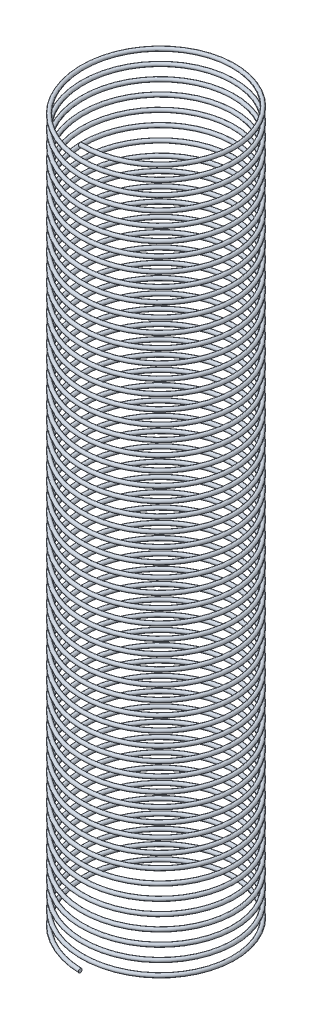
SolidWorks part; units mm, degrees
ref_plane "Front Plane" through (0, 0, 0) normal (0, 0, 1) x (1, 0, 0)
ref_plane "Top Plane" through (0, 0, 0) normal (0, 1, 0) x (1, 0, 0)
ref_plane "Right Plane" through (0, 0, 0) normal (1, 0, 0) x (0, 0, -1)
sketch "Sketch1" plane through (0, 0, 0) normal (0, 1, 0) x (1, 0, 0)
  circle A0 centre (0, 0) radius 2
  dimension "D1" = 4
curve "Helix/Spiral1" pitch 0.35 height 18.9 turns 54
sketch "Sketch2" plane through (0, 0, 0) normal (1, 0, 0) x (0, 0, -1)
  circle A0 centre (-2, 0) radius 0.05
  spline S0 degree 3 poles (-2, 0) (-2, 0.0072) (-1.8959, 0.0219) (-1.451, 0.0437) (-0.7853, 0.0656) (0, 0.0875) (0.7853, 0.1094) (1.451, 0.1312) (1.8959, 0.1531) (2.0521, 0.175) (1.8959, 0.1969) (1.451, 0.2187) (0.7853, 0.2406) (0, 0.2625) (-0.7853, 0.2844) (-1.451, 0.3062) (-1.8959, 0.3281) (-2.0521, 0.35) (-1.8959, 0.3719) (-1.451, 0.3937) (-0.7853, 0.4156) (0, 0.4375) (0.7853, 0.4594) (1.451, 0.4812) (1.8959, 0.5031) (2.0521, 0.525) (1.8959, 0.5469) (1.451, 0.5687) (0.7853, 0.5906) (0, 0.6125) (-0.7853, 0.6344) (-1.451, 0.6562) (-1.8959, 0.6781) (-2.0521, 0.7) (-1.8959, 0.7219) (-1.451, 0.7437) (-0.7853, 0.7656) (0, 0.7875) (0.7853, 0.8094) (1.451, 0.8312) (1.8959, 0.8531) (2.0521, 0.875) (1.8959, 0.8969) (1.451, 0.9187) (0.7853, 0.9406) (0, 0.9625) (-0.7853, 0.9844) (-1.451, 1.0062) (-1.8959, 1.0281) (-2.0521, 1.05) (-1.8959, 1.0719) (-1.451, 1.0937) (-0.7853, 1.1156) (0, 1.1375) (0.7853, 1.1594) (1.451, 1.1812) (1.8959, 1.2031) (2.0521, 1.225) (1.8959, 1.2469) (1.451, 1.2687) (0.7853, 1.2906) (0, 1.3125) (-0.7853, 1.3344) (-1.451, 1.3562) (-1.8959, 1.3781) (-2.0521, 1.4) (-1.8959, 1.4219) (-1.451, 1.4437) (-0.7853, 1.4656) (0, 1.4875) (0.7853, 1.5094) (1.451, 1.5312) (1.8959, 1.5531) (2.0521, 1.575) (1.8959, 1.5969) (1.451, 1.6187) (0.7853, 1.6406) (0, 1.6625) (-0.7853, 1.6844) (-1.451, 1.7062) (-1.8959, 1.7281) (-2.0521, 1.75) (-1.8959, 1.7719) (-1.451, 1.7937) (-0.7853, 1.8156) (0, 1.8375) (0.7853, 1.8594) (1.451, 1.8812) (1.8959, 1.9031) (2.0521, 1.925) (1.8959, 1.9469) (1.451, 1.9687) (0.7853, 1.9906) (0, 2.0125) (-0.7853, 2.0344) (-1.451, 2.0562) (-1.8959, 2.0781) (-2.0521, 2.1) (-1.8959, 2.1219) (-1.451, 2.1437) (-0.7853, 2.1656) (0, 2.1875) (0.7853, 2.2094) (1.451, 2.2313) (1.8959, 2.2531) (2.0521, 2.275) (1.8959, 2.2969) (1.451, 2.3188) (0.7853, 2.3406) (0, 2.3625) (-0.7853, 2.3844) (-1.451, 2.4063) (-1.8959, 2.4281) (-2.0521, 2.45) (-1.8959, 2.4719) (-1.451, 2.4938) (-0.7853, 2.5156) (0, 2.5375) (0.7853, 2.5594) (1.451, 2.5813) (1.8959, 2.6031) (2.0521, 2.625) (1.8959, 2.6469) (1.451, 2.6688) (0.7853, 2.6906) (0, 2.7125) (-0.7853, 2.7344) (-1.451, 2.7563) (-1.8959, 2.7781) (-2.0521, 2.8) (-1.8959, 2.8219) (-1.451, 2.8438) (-0.7853, 2.8656) (0, 2.8875) (0.7853, 2.9094) (1.451, 2.9313) (1.8959, 2.9531) (2.0521, 2.975) (1.8959, 2.9969) (1.451, 3.0188) (0.7853, 3.0406) (0, 3.0625) (-0.7853, 3.0844) (-1.451, 3.1063) (-1.8959, 3.1281) (-2.0521, 3.15) (-1.8959, 3.1719) (-1.451, 3.1938) (-0.7853, 3.2156) (0, 3.2375) (0.7853, 3.2594) (1.451, 3.2813) (1.8959, 3.3031) (2.0521, 3.325) (1.8959, 3.3469) (1.451, 3.3688) (0.7853, 3.3906) (0, 3.4125) (-0.7853, 3.4344) (-1.451, 3.4563) (-1.8959, 3.4781) (-2.0521, 3.5) (-1.8959, 3.5219) (-1.451, 3.5438) (-0.7853, 3.5656) (0, 3.5875) (0.7853, 3.6094) (1.451, 3.6313) (1.8959, 3.6531) (2.0521, 3.675) (1.8959, 3.6969) (1.451, 3.7188) (0.7853, 3.7406) (0, 3.7625) (-0.7853, 3.7844) (-1.451, 3.8063) (-1.8959, 3.8281) (-2.0521, 3.85) (-1.8959, 3.8719) (-1.451, 3.8938) (-0.7853, 3.9156) (0, 3.9375) (0.7853, 3.9594) (1.451, 3.9813) (1.8959, 4.0031) (2.0521, 4.025) (1.8959, 4.0469) (1.451, 4.0688) (0.7853, 4.0906) (0, 4.1125) (-0.7853, 4.1344) (-1.451, 4.1563) (-1.8959, 4.1781) (-2.0521, 4.2) (-1.8959, 4.2219) (-1.451, 4.2438) (-0.7853, 4.2656) (0, 4.2875) (0.7853, 4.3094) (1.451, 4.3313) (1.8959, 4.3531) (2.0521, 4.375) (1.8959, 4.3969) (1.451, 4.4188) (0.7853, 4.4406) (0, 4.4625) (-0.7853, 4.4844) (-1.451, 4.5063) (-1.8959, 4.5281) (-2.0521, 4.55) (-1.8959, 4.5719) (-1.451, 4.5938) (-0.7853, 4.6156) (0, 4.6375) (0.7853, 4.6594) (1.451, 4.6813) (1.8959, 4.7031) (2.0521, 4.725) (1.8959, 4.7469) (1.451, 4.7688) (0.7853, 4.7906) (0, 4.8125) (-0.7853, 4.8344) (-1.451, 4.8563) (-1.8959, 4.8781) (-2.0521, 4.9) (-1.8959, 4.9219) (-1.451, 4.9438) (-0.7853, 4.9656) (0, 4.9875) (0.7853, 5.0094) (1.451, 5.0313) (1.8959, 5.0531) (2.0521, 5.075) (1.8959, 5.0969) (1.451, 5.1188) (0.7853, 5.1406) (0, 5.1625) (-0.7853, 5.1844) (-1.451, 5.2063) (-1.8959, 5.2281) (-2.0521, 5.25) (-1.8959, 5.2719) (-1.451, 5.2938) (-0.7853, 5.3156) (0, 5.3375) (0.7853, 5.3594) (1.451, 5.3813) (1.8959, 5.4031) (2.0521, 5.425) (1.8959, 5.4469) (1.451, 5.4688) (0.7853, 5.4906) (0, 5.5125) (-0.7853, 5.5344) (-1.451, 5.5563) (-1.8959, 5.5781) (-2.0521, 5.6) (-1.8959, 5.6219) (-1.451, 5.6438) (-0.7853, 5.6656) (0, 5.6875) (0.7853, 5.7094) (1.451, 5.7313) (1.8959, 5.7531) (2.0521, 5.775) (1.8959, 5.7969) (1.451, 5.8188) (0.7853, 5.8406) (0, 5.8625) (-0.7853, 5.8844) (-1.451, 5.9063) (-1.8959, 5.9281) (-2.0521, 5.95) (-1.8959, 5.9719) (-1.451, 5.9938) (-0.7853, 6.0156) (0, 6.0375) (0.7853, 6.0594) (1.451, 6.0813) (1.8959, 6.1031) (2.0521, 6.125) (1.8959, 6.1469) (1.451, 6.1688) (0.7853, 6.1906) (0, 6.2125) (-0.7853, 6.2344) (-1.451, 6.2563) (-1.8959, 6.2781) (-2.0521, 6.3) (-1.8959, 6.3219) (-1.451, 6.3438) (-0.7853, 6.3656) (0, 6.3875) (0.7853, 6.4094) (1.451, 6.4313) (1.8959, 6.4531) (2.0521, 6.475) (1.8959, 6.4969) (1.451, 6.5188) (0.7853, 6.5406) (0, 6.5625) (-0.7853, 6.5844) (-1.451, 6.6063) (-1.8959, 6.6281) (-2.0521, 6.65) (-1.8959, 6.6719) (-1.451, 6.6938) (-0.7853, 6.7156) (0, 6.7375) (0.7853, 6.7594) (1.451, 6.7813) (1.8959, 6.8031) (2.0521, 6.825) (1.8959, 6.8469) (1.451, 6.8688) (0.7853, 6.8906) (0, 6.9125) (-0.7853, 6.9344) (-1.451, 6.9563) (-1.8959, 6.9781) (-2.0521, 7) (-1.8959, 7.0219) (-1.451, 7.0438) (-0.7853, 7.0656) (0, 7.0875) (0.7853, 7.1094) (1.451, 7.1313) (1.8959, 7.1531) (2.0521, 7.175) (1.8959, 7.1969) (1.451, 7.2188) (0.7853, 7.2406) (0, 7.2625) (-0.7853, 7.2844) (-1.451, 7.3063) (-1.8959, 7.3281) (-2.0521, 7.35) (-1.8959, 7.3719) (-1.451, 7.3938) (-0.7853, 7.4156) (0, 7.4375) (0.7853, 7.4594) (1.451, 7.4813) (1.8959, 7.5031) (2.0521, 7.525) (1.8959, 7.5469) (1.451, 7.5688) (0.7853, 7.5906) (0, 7.6125) (-0.7853, 7.6344) (-1.451, 7.6563) (-1.8959, 7.6781) (-2.0521, 7.7) (-1.8959, 7.7219) (-1.451, 7.7438) (-0.7853, 7.7656) (0, 7.7875) (0.7853, 7.8094) (1.451, 7.8313) (1.8959, 7.8531) (2.0521, 7.875) (1.8959, 7.8969) (1.451, 7.9188) (0.7853, 7.9406) (0, 7.9625) (-0.7853, 7.9844) (-1.451, 8.0063) (-1.8959, 8.0281) (-2.0521, 8.05) (-1.8959, 8.0719) (-1.451, 8.0938) (-0.7853, 8.1156) (0, 8.1375) (0.7853, 8.1594) (1.451, 8.1813) (1.8959, 8.2031) (2.0521, 8.225) (1.8959, 8.2469) (1.451, 8.2688) (0.7853, 8.2906) (0, 8.3125) (-0.7853, 8.3344) (-1.451, 8.3563) (-1.8959, 8.3781) (-2.0521, 8.4) (-1.8959, 8.4219) (-1.451, 8.4438) (-0.7853, 8.4656) (0, 8.4875) (0.7853, 8.5094) (1.451, 8.5313) (1.8959, 8.5531) (2.0521, 8.575) (1.8959, 8.5969) (1.451, 8.6188) (0.7853, 8.6406) (0, 8.6625) (-0.7853, 8.6844) (-1.451, 8.7063) (-1.8959, 8.7281) (-2.0521, 8.75) (-1.8959, 8.7719) (-1.451, 8.7938) (-0.7853, 8.8156) (0, 8.8375) (0.7853, 8.8594) (1.451, 8.8813) (1.8959, 8.9031) (2.0521, 8.925) (1.8959, 8.9469) (1.451, 8.9688) (0.7853, 8.9906) (0, 9.0125) (-0.7853, 9.0344) (-1.451, 9.0563) (-1.8959, 9.0781) (-2.0521, 9.1) (-1.8959, 9.1219) (-1.451, 9.1438) (-0.7853, 9.1656) (0, 9.1875) (0.7853, 9.2094) (1.451, 9.2313) (1.8959, 9.2531) (2.0521, 9.275) (1.8959, 9.2969) (1.451, 9.3188) (0.7853, 9.3406) (0, 9.3625) (-0.7853, 9.3844) (-1.451, 9.4062) (-1.8959, 9.4281) (-2.0521, 9.45) (-1.8959, 9.4719) (-1.451, 9.4937) (-0.7853, 9.5156) (0, 9.5375) (0.7853, 9.5594) (1.451, 9.5812) (1.8959, 9.6031) (2.0521, 9.625) (1.8959, 9.6469) (1.451, 9.6687) (0.7853, 9.6906) (0, 9.7125) (-0.7853, 9.7344) (-1.451, 9.7562) (-1.8959, 9.7781) (-2.0521, 9.8) (-1.8959, 9.8219) (-1.451, 9.8437) (-0.7853, 9.8656) (0, 9.8875) (0.7853, 9.9094) (1.451, 9.9312) (1.8959, 9.9531) (2.0521, 9.975) (1.8959, 9.9969) (1.451, 10.0187) (0.7853, 10.0406) (0, 10.0625) (-0.7853, 10.0844) (-1.451, 10.1062) (-1.8959, 10.1281) (-2.0521, 10.15) (-1.8959, 10.1719) (-1.451, 10.1937) (-0.7853, 10.2156) (0, 10.2375) (0.7853, 10.2594) (1.451, 10.2812) (1.8959, 10.3031) (2.0521, 10.325) (1.8959, 10.3469) (1.451, 10.3687) (0.7853, 10.3906) (0, 10.4125) (-0.7853, 10.4344) (-1.451, 10.4562) (-1.8959, 10.4781) (-2.0521, 10.5) (-1.8959, 10.5219) (-1.451, 10.5437) (-0.7853, 10.5656) (0, 10.5875) (0.7853, 10.6094) (1.451, 10.6312) (1.8959, 10.6531) (2.0521, 10.675) (1.8959, 10.6969) (1.451, 10.7187) (0.7853, 10.7406) (0, 10.7625) (-0.7853, 10.7844) (-1.451, 10.8062) (-1.8959, 10.8281) (-2.0521, 10.85) (-1.8959, 10.8719) (-1.451, 10.8937) (-0.7853, 10.9156) (0, 10.9375) (0.7853, 10.9594) (1.451, 10.9812) (1.8959, 11.0031) (2.0521, 11.025) (1.8959, 11.0469) (1.451, 11.0687) (0.7853, 11.0906) (0, 11.1125) (-0.7853, 11.1344) (-1.451, 11.1562) (-1.8959, 11.1781) (-2.0521, 11.2) (-1.8959, 11.2219) (-1.451, 11.2437) (-0.7853, 11.2656) (0, 11.2875) (0.7853, 11.3094) (1.451, 11.3312) (1.8959, 11.3531) (2.0521, 11.375) (1.8959, 11.3969) (1.451, 11.4187) (0.7853, 11.4406) (0, 11.4625) (-0.7853, 11.4844) (-1.451, 11.5062) (-1.8959, 11.5281) (-2.0521, 11.55) (-1.8959, 11.5719) (-1.451, 11.5937) (-0.7853, 11.6156) (0, 11.6375) (0.7853, 11.6594) (1.451, 11.6812) (1.8959, 11.7031) (2.0521, 11.725) (1.8959, 11.7469) (1.451, 11.7687) (0.7853, 11.7906) (0, 11.8125) (-0.7853, 11.8344) (-1.451, 11.8562) (-1.8959, 11.8781) (-2.0521, 11.9) (-1.8959, 11.9219) (-1.451, 11.9437) (-0.7853, 11.9656) (0, 11.9875) (0.7853, 12.0094) (1.451, 12.0312) (1.8959, 12.0531) (2.0521, 12.075) (1.8959, 12.0969) (1.451, 12.1187) (0.7853, 12.1406) (0, 12.1625) (-0.7853, 12.1844) (-1.451, 12.2062) (-1.8959, 12.2281) (-2.0521, 12.25) (-1.8959, 12.2719) (-1.451, 12.2937) (-0.7853, 12.3156) (0, 12.3375) (0.7853, 12.3594) (1.451, 12.3812) (1.8959, 12.4031) (2.0521, 12.425) (1.8959, 12.4469) (1.451, 12.4687) (0.7853, 12.4906) (0, 12.5125) (-0.7853, 12.5344) (-1.451, 12.5562) (-1.8959, 12.5781) (-2.0521, 12.6) (-1.8959, 12.6219) (-1.451, 12.6437) (-0.7853, 12.6656) (0, 12.6875) (0.7853, 12.7094) (1.451, 12.7312) (1.8959, 12.7531) (2.0521, 12.775) (1.8959, 12.7969) (1.451, 12.8187) (0.7853, 12.8406) (0, 12.8625) (-0.7853, 12.8844) (-1.451, 12.9062) (-1.8959, 12.9281) (-2.0521, 12.95) (-1.8959, 12.9719) (-1.451, 12.9937) (-0.7853, 13.0156) (0, 13.0375) (0.7853, 13.0594) (1.451, 13.0812) (1.8959, 13.1031) (2.0521, 13.125) (1.8959, 13.1469) (1.451, 13.1687) (0.7853, 13.1906) (0, 13.2125) (-0.7853, 13.2344) (-1.451, 13.2562) (-1.8959, 13.2781) (-2.0521, 13.3) (-1.8959, 13.3219) (-1.451, 13.3437) (-0.7853, 13.3656) (0, 13.3875) (0.7853, 13.4094) (1.451, 13.4312) (1.8959, 13.4531) (2.0521, 13.475) (1.8959, 13.4969) (1.451, 13.5187) (0.7853, 13.5406) (0, 13.5625) (-0.7853, 13.5844) (-1.451, 13.6062) (-1.8959, 13.6281) (-2.0521, 13.65) (-1.8959, 13.6719) (-1.451, 13.6937) (-0.7853, 13.7156) (0, 13.7375) (0.7853, 13.7594) (1.451, 13.7812) (1.8959, 13.8031) (2.0521, 13.825) (1.8959, 13.8469) (1.451, 13.8687) (0.7853, 13.8906) (0, 13.9125) (-0.7853, 13.9344) (-1.451, 13.9562) (-1.8959, 13.9781) (-2.0521, 14) (-1.8959, 14.0219) (-1.451, 14.0437) (-0.7853, 14.0656) (0, 14.0875) (0.7853, 14.1094) (1.451, 14.1312) (1.8959, 14.1531) (2.0521, 14.175) (1.8959, 14.1969) (1.451, 14.2187) (0.7853, 14.2406) (0, 14.2625) (-0.7853, 14.2844) (-1.451, 14.3062) (-1.8959, 14.3281) (-2.0521, 14.35) (-1.8959, 14.3719) (-1.451, 14.3937) (-0.7853, 14.4156) (0, 14.4375) (0.7853, 14.4594) (1.451, 14.4812) (1.8959, 14.5031) (2.0521, 14.525) (1.8959, 14.5469) (1.451, 14.5687) (0.7853, 14.5906) (0, 14.6125) (-0.7853, 14.6344) (-1.451, 14.6562) (-1.8959, 14.6781) (-2.0521, 14.7) (-1.8959, 14.7219) (-1.451, 14.7437) (-0.7853, 14.7656) (0, 14.7875) (0.7853, 14.8094) (1.451, 14.8312) (1.8959, 14.8531) (2.0521, 14.875) (1.8959, 14.8969) (1.451, 14.9187) (0.7853, 14.9406) (0, 14.9625) (-0.7853, 14.9844) (-1.451, 15.0062) (-1.8959, 15.0281) (-2.0521, 15.05) (-1.8959, 15.0719) (-1.451, 15.0937) (-0.7853, 15.1156) (0, 15.1375) (0.7853, 15.1594) (1.451, 15.1812) (1.8959, 15.2031) (2.0521, 15.225) (1.8959, 15.2469) (1.451, 15.2687) (0.7853, 15.2906) (0, 15.3125) (-0.7853, 15.3344) (-1.451, 15.3562) (-1.8959, 15.3781) (-2.0521, 15.4) (-1.8959, 15.4219) (-1.451, 15.4437) (-0.7853, 15.4656) (0, 15.4875) (0.7853, 15.5094) (1.451, 15.5312) (1.8959, 15.5531) (2.0521, 15.575) (1.8959, 15.5969) (1.451, 15.6187) (0.7853, 15.6406) (0, 15.6625) (-0.7853, 15.6844) (-1.451, 15.7062) (-1.8959, 15.7281) (-2.0521, 15.75) (-1.8959, 15.7719) (-1.451, 15.7937) (-0.7853, 15.8156) (0, 15.8375) (0.7853, 15.8594) (1.451, 15.8812) (1.8959, 15.9031) (2.0521, 15.925) (1.8959, 15.9469) (1.451, 15.9687) (0.7853, 15.9906) (0, 16.0125) (-0.7853, 16.0344) (-1.451, 16.0562) (-1.8959, 16.0781) (-2.0521, 16.1) (-1.8959, 16.1219) (-1.451, 16.1437) (-0.7853, 16.1656) (0, 16.1875) (0.7853, 16.2094) (1.451, 16.2312) (1.8959, 16.2531) (2.0521, 16.275) (1.8959, 16.2969) (1.451, 16.3187) (0.7853, 16.3406) (0, 16.3625) (-0.7853, 16.3844) (-1.451, 16.4062) (-1.8959, 16.4281) (-2.0521, 16.45) (-1.8959, 16.4719) (-1.451, 16.4937) (-0.7853, 16.5156) (0, 16.5375) (0.7853, 16.5594) (1.451, 16.5812) (1.8959, 16.6031) (2.0521, 16.625) (1.8959, 16.6469) (1.451, 16.6687) (0.7853, 16.6906) (0, 16.7125) (-0.7853, 16.7344) (-1.451, 16.7562) (-1.8959, 16.7781) (-2.0521, 16.8) (-1.8959, 16.8219) (-1.451, 16.8437) (-0.7853, 16.8656) (0, 16.8875) (0.7853, 16.9094) (1.451, 16.9312) (1.8959, 16.9531) (2.0521, 16.975) (1.8959, 16.9969) (1.451, 17.0187) (0.7853, 17.0406) (0, 17.0625) (-0.7853, 17.0844) (-1.451, 17.1062) (-1.8959, 17.1281) (-2.0521, 17.15) (-1.8959, 17.1719) (-1.451, 17.1937) (-0.7853, 17.2156) (0, 17.2375) (0.7853, 17.2594) (1.451, 17.2812) (1.8959, 17.3031) (2.0521, 17.325) (1.8959, 17.3469) (1.451, 17.3687) (0.7853, 17.3906) (0, 17.4125) (-0.7853, 17.4344) (-1.451, 17.4562) (-1.8959, 17.4781) (-2.0521, 17.5) (-1.8959, 17.5219) (-1.451, 17.5437) (-0.7853, 17.5656) (0, 17.5875) (0.7853, 17.6094) (1.451, 17.6312) (1.8959, 17.6531) (2.0521, 17.675) (1.8959, 17.6969) (1.451, 17.7187) (0.7853, 17.7406) (0, 17.7625) (-0.7853, 17.7844) (-1.451, 17.8062) (-1.8959, 17.8281) (-2.0521, 17.85) (-1.8959, 17.8719) (-1.451, 17.8937) (-0.7853, 17.9156) (0, 17.9375) (0.7853, 17.9594) (1.451, 17.9812) (1.8959, 18.0031) (2.0521, 18.025) (1.8959, 18.0469) (1.451, 18.0687) (0.7853, 18.0906) (0, 18.1125) (-0.7853, 18.1344) (-1.451, 18.1562) (-1.8959, 18.1781) (-2.0521, 18.2) (-1.8959, 18.2219) (-1.451, 18.2437) (-0.7853, 18.2656) (0, 18.2875) (0.7853, 18.3094) (1.451, 18.3312) (1.8959, 18.3531) (2.0521, 18.375) (1.8959, 18.3969) (1.451, 18.4187) (0.7853, 18.4406) (0, 18.4625) (-0.7853, 18.4844) (-1.451, 18.5062) (-1.8959, 18.5281) (-2.0521, 18.55) (-1.8959, 18.5719) (-1.451, 18.5938) (-0.7853, 18.6156) (0, 18.6375) (0.7853, 18.6594) (1.451, 18.6813) (1.8959, 18.7031) (2.0521, 18.725) (1.8959, 18.7469) (1.451, 18.7688) (0.7853, 18.7906) (0, 18.8125) (-0.7853, 18.8344) (-1.451, 18.8563) (-1.8959, 18.8781) (-2, 18.8928) (-2, 18.9) knots 0 0 0 0 0.001157 0.002315 0.003472 0.00463 0.005787 0.006944 0.008102 0.009259 0.010417 0.011574 0.012731 0.013889 0.015046 0.016204 0.017361 0.018519 0.019676 0.020833 0.021991 0.023148 0.024306 0.025463 0.02662 0.027778 0.028935 0.030093 0.03125 0.032407 0.033565 0.034722 0.03588 0.037037 0.038194 0.039352 0.040509 0.041667 0.042824 0.043981 0.045139 0.046296 0.047454 0.048611 0.049769 0.050926 0.052083 0.053241 0.054398 0.055556 0.056713 0.05787 0.059028 0.060185 0.061343 0.0625 0.063657 0.064815 0.065972 0.06713 0.068287 0.069444 0.070602 0.071759 0.072917 0.074074 0.075231 0.076389 0.077546 0.078704 0.079861 0.081019 0.082176 0.083333 0.084491 0.085648 0.086806 0.087963 0.08912 0.090278 0.091435 0.092593 0.09375 0.094907 0.096065 0.097222 0.09838 0.099537 0.100694 0.101852 0.103009 0.104167 0.105324 0.106481 0.107639 0.108796 0.109954 0.111111 0.112269 0.113426 0.114583 0.115741 0.116898 0.118056 0.119213 0.12037 0.121528 0.122685 0.123843 0.125 0.126157 0.127315 0.128472 0.12963 0.130787 0.131944 0.133102 0.134259 0.135417 0.136574 0.137731 0.138889 0.140046 0.141204 0.142361 0.143519 0.144676 0.145833 0.146991 0.148148 0.149306 0.150463 0.15162 0.152778 0.153935 0.155093 0.15625 0.157407 0.158565 0.159722 0.16088 0.162037 0.163194 0.164352 0.165509 0.166667 0.167824 0.168981 0.170139 0.171296 0.172454 0.173611 0.174769 0.175926 0.177083 0.178241 0.179398 0.180556 0.181713 0.18287 0.184028 0.185185 0.186343 0.1875 0.188657 0.189815 0.190972 0.19213 0.193287 0.194444 0.195602 0.196759 0.197917 0.199074 0.200231 0.201389 0.202546 0.203704 0.204861 0.206019 0.207176 0.208333 0.209491 0.210648 0.211806 0.212963 0.21412 0.215278 0.216435 0.217593 0.21875 0.219907 0.221065 0.222222 0.22338 0.224537 0.225694 0.226852 0.228009 0.229167 0.230324 0.231481 0.232639 0.233796 0.234954 0.236111 0.237269 0.238426 0.239583 0.240741 0.241898 0.243056 0.244213 0.24537 0.246528 0.247685 0.248843 0.25 0.251157 0.252315 0.253472 0.25463 0.255787 0.256944 0.258102 0.259259 0.260417 0.261574 0.262731 0.263889 0.265046 0.266204 0.267361 0.268519 0.269676 0.270833 0.271991 0.273148 0.274306 0.275463 0.27662 0.277778 0.278935 0.280093 0.28125 0.282407 0.283565 0.284722 0.28588 0.287037 0.288194 0.289352 0.290509 0.291667 0.292824 0.293981 0.295139 0.296296 0.297454 0.298611 0.299769 0.300926 0.302083 0.303241 0.304398 0.305556 0.306713 0.30787 0.309028 0.310185 0.311343 0.3125 0.313657 0.314815 0.315972 0.31713 0.318287 0.319444 0.320602 0.321759 0.322917 0.324074 0.325231 0.326389 0.327546 0.328704 0.329861 0.331019 0.332176 0.333333 0.334491 0.335648 0.336806 0.337963 0.33912 0.340278 0.341435 0.342593 0.34375 0.344907 0.346065 0.347222 0.34838 0.349537 0.350694 0.351852 0.353009 0.354167 0.355324 0.356481 0.357639 0.358796 0.359954 0.361111 0.362269 0.363426 0.364583 0.365741 0.366898 0.368056 0.369213 0.37037 0.371528 0.372685 0.373843 0.375 0.376157 0.377315 0.378472 0.37963 0.380787 0.381944 0.383102 0.384259 0.385417 0.386574 0.387731 0.388889 0.390046 0.391204 0.392361 0.393519 0.394676 0.395833 0.396991 0.398148 0.399306 0.400463 0.40162 0.402778 0.403935 0.405093 0.40625 0.407407 0.408565 0.409722 0.41088 0.412037 0.413194 0.414352 0.415509 0.416667 0.417824 0.418981 0.420139 0.421296 0.422454 0.423611 0.424769 0.425926 0.427083 0.428241 0.429398 0.430556 0.431713 0.43287 0.434028 0.435185 0.436343 0.4375 0.438657 0.439815 0.440972 0.44213 0.443287 0.444444 0.445602 0.446759 0.447917 0.449074 0.450231 0.451389 0.452546 0.453704 0.454861 0.456019 0.457176 0.458333 0.459491 0.460648 0.461806 0.462963 0.46412 0.465278 0.466435 0.467593 0.46875 0.469907 0.471065 0.472222 0.47338 0.474537 0.475694 0.476852 0.478009 0.479167 0.480324 0.481481 0.482639 0.483796 0.484954 0.486111 0.487269 0.488426 0.489583 0.490741 0.491898 0.493056 0.494213 0.49537 0.496528 0.497685 0.498843 0.5 0.501157 0.502315 0.503472 0.50463 0.505787 0.506944 0.508102 0.509259 0.510417 0.511574 0.512731 0.513889 0.515046 0.516204 0.517361 0.518519 0.519676 0.520833 0.521991 0.523148 0.524306 0.525463 0.52662 0.527778 0.528935 0.530093 0.53125 0.532407 0.533565 0.534722 0.53588 0.537037 0.538194 0.539352 0.540509 0.541667 0.542824 0.543981 0.545139 0.546296 0.547454 0.548611 0.549769 0.550926 0.552083 0.553241 0.554398 0.555556 0.556713 0.55787 0.559028 0.560185 0.561343 0.5625 0.563657 0.564815 0.565972 0.56713 0.568287 0.569444 0.570602 0.571759 0.572917 0.574074 0.575231 0.576389 0.577546 0.578704 0.579861 0.581019 0.582176 0.583333 0.584491 0.585648 0.586806 0.587963 0.58912 0.590278 0.591435 0.592593 0.59375 0.594907 0.596065 0.597222 0.59838 0.599537 0.600694 0.601852 0.603009 0.604167 0.605324 0.606481 0.607639 0.608796 0.609954 0.611111 0.612269 0.613426 0.614583 0.615741 0.616898 0.618056 0.619213 0.62037 0.621528 0.622685 0.623843 0.625 0.626157 0.627315 0.628472 0.62963 0.630787 0.631944 0.633102 0.634259 0.635417 0.636574 0.637731 0.638889 0.640046 0.641204 0.642361 0.643519 0.644676 0.645833 0.646991 0.648148 0.649306 0.650463 0.65162 0.652778 0.653935 0.655093 0.65625 0.657407 0.658565 0.659722 0.66088 0.662037 0.663194 0.664352 0.665509 0.666667 0.667824 0.668981 0.670139 0.671296 0.672454 0.673611 0.674769 0.675926 0.677083 0.678241 0.679398 0.680556 0.681713 0.68287 0.684028 0.685185 0.686343 0.6875 0.688657 0.689815 0.690972 0.69213 0.693287 0.694444 0.695602 0.696759 0.697917 0.699074 0.700231 0.701389 0.702546 0.703704 0.704861 0.706019 0.707176 0.708333 0.709491 0.710648 0.711806 0.712963 0.71412 0.715278 0.716435 0.717593 0.71875 0.719907 0.721065 0.722222 0.72338 0.724537 0.725694 0.726852 0.728009 0.729167 0.730324 0.731481 0.732639 0.733796 0.734954 0.736111 0.737269 0.738426 0.739583 0.740741 0.741898 0.743056 0.744213 0.74537 0.746528 0.747685 0.748843 0.75 0.751157 0.752315 0.753472 0.75463 0.755787 0.756944 0.758102 0.759259 0.760417 0.761574 0.762731 0.763889 0.765046 0.766204 0.767361 0.768519 0.769676 0.770833 0.771991 0.773148 0.774306 0.775463 0.77662 0.777778 0.778935 0.780093 0.78125 0.782407 0.783565 0.784722 0.78588 0.787037 0.788194 0.789352 0.790509 0.791667 0.792824 0.793981 0.795139 0.796296 0.797454 0.798611 0.799769 0.800926 0.802083 0.803241 0.804398 0.805556 0.806713 0.80787 0.809028 0.810185 0.811343 0.8125 0.813657 0.814815 0.815972 0.81713 0.818287 0.819444 0.820602 0.821759 0.822917 0.824074 0.825231 0.826389 0.827546 0.828704 0.829861 0.831019 0.832176 0.833333 0.834491 0.835648 0.836806 0.837963 0.83912 0.840278 0.841435 0.842593 0.84375 0.844907 0.846065 0.847222 0.84838 0.849537 0.850694 0.851852 0.853009 0.854167 0.855324 0.856481 0.857639 0.858796 0.859954 0.861111 0.862269 0.863426 0.864583 0.865741 0.866898 0.868056 0.869213 0.87037 0.871528 0.872685 0.873843 0.875 0.876157 0.877315 0.878472 0.87963 0.880787 0.881944 0.883102 0.884259 0.885417 0.886574 0.887731 0.888889 0.890046 0.891204 0.892361 0.893519 0.894676 0.895833 0.896991 0.898148 0.899306 0.900463 0.90162 0.902778 0.903935 0.905093 0.90625 0.907407 0.908565 0.909722 0.91088 0.912037 0.913194 0.914352 0.915509 0.916667 0.917824 0.918981 0.920139 0.921296 0.922454 0.923611 0.924769 0.925926 0.927083 0.928241 0.929398 0.930556 0.931713 0.93287 0.934028 0.935185 0.936343 0.9375 0.938657 0.939815 0.940972 0.94213 0.943287 0.944444 0.945602 0.946759 0.947917 0.949074 0.950231 0.951389 0.952546 0.953704 0.954861 0.956019 0.957176 0.958333 0.959491 0.960648 0.961806 0.962963 0.96412 0.965278 0.966435 0.967593 0.96875 0.969907 0.971065 0.972222 0.97338 0.974537 0.975694 0.976852 0.978009 0.979167 0.980324 0.981481 0.982639 0.983796 0.984954 0.986111 0.987269 0.988426 0.989583 0.990741 0.991898 0.993056 0.994213 0.99537 0.996528 0.997685 0.998843 1 1 1 1 construction
sweep "Sweep1" add profiles "Sketch2" path "Helix/Spiral1"
